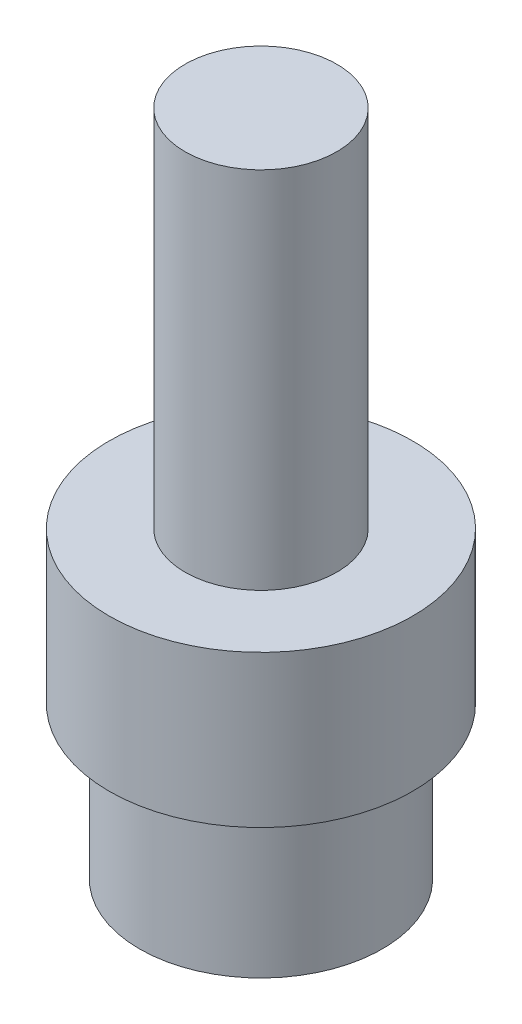
SolidWorks part; units mm, degrees
ref_plane "Front Plane" through (0, 0, 0) normal (0, 0, 1) x (1, 0, 0)
ref_plane "Top Plane" through (0, 0, 0) normal (0, 1, 0) x (1, 0, 0)
ref_plane "Right Plane" through (0, 0, 0) normal (1, 0, 0) x (0, 0, -1)
sketch "Sketch1" plane through (0, 0, 0) normal (0, 1, 0) x (1, 0, 0)
  circle A0 centre (0, 0) radius 5
  dimension "D1" = 10
extrude "Boss-Extrude1" add sketch "Sketch1" along normal blind 5
sketch "Sketch2" plane through (0, 0, 0) normal (0, -1, 0) x (1, 0, 0)
  circle A0 centre (0, 0) radius 4
  dimension "D1" = 8
extrude "Boss-Extrude2" add sketch "Sketch2" along normal blind 5
sketch "Sketch3" plane through (0, 5, 0) normal (0, 1, 0) x (1, 0, 0)
  circle A0 centre (0, 0) radius 2.5
  dimension "D1" = 5
extrude "Boss-Extrude3" add sketch "Sketch3" along normal blind 12
